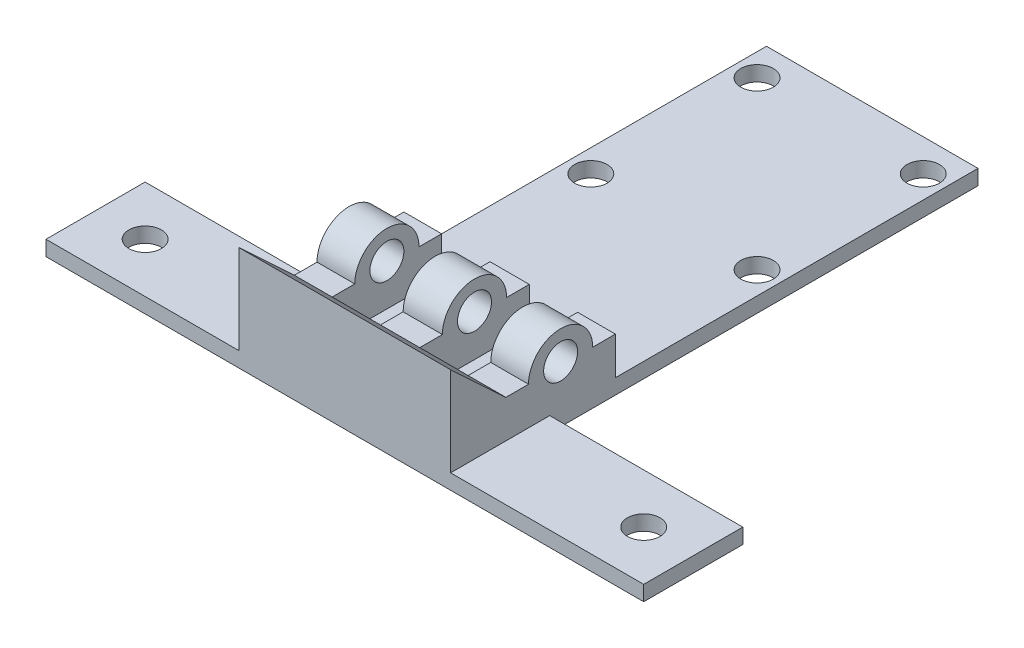
SolidWorks part; units mm, degrees
ref_plane "Front Plane" through (0, 0, 0) normal (0, 0, 1) x (1, 0, 0)
ref_plane "Top Plane" through (0, 0, 0) normal (0, 1, 0) x (1, 0, 0)
ref_plane "Right Plane" through (0, 0, 0) normal (1, 0, 0) x (0, 0, -1)
sketch "Sketch1" plane through (0, 0, 0) normal (1, 0, 0) x (0, 0, -1)
  line L0 (2.25, 1.5) -> (7.25, 1.5)
  line L1 (-2.25, -1.5) -> (2.25, -1.5)
  line L2 (-2.25, -1.5) -> (-2.25, 1.5)
  line L3 (-2.25, 1.5) -> (2.25, 1.5) construction
  line L4 (2.25, -1.5) -> (2.25, 1.5)
  line L5 (-2.25, -1.5) -> (2.25, 1.5) construction
  line L6 (-2.25, 1.5) -> (2.25, -1.5) construction
  line L7 (7.25, 1.5) -> (7.25, 8.5)
  line L8 (7.25, 8.5) -> (4.25, 8.5)
  line L9 (-2.25, 1.5) -> (-7.25, 1.5)
  line L10 (-7.25, 1.5) -> (-7.25, 8.5)
  line L11 (-7.25, 8.5) -> (-4.25, 8.5)
  line L12 (0, 1.5) -> (0, 9) construction
  line L13 (0, 11.25) -> (0, 12.75) construction
  circle A0 centre (0, 9) radius 2.25
  arc A1 (-4.25, 8.5) -> (4.25, 8.5) centre (0, 8.5) cw
  point P0 (0, 0)
  dimension "D10" = 4.5
  dimension "D11" = 1.5
  dimension "D1" = 3
  dimension "D2" = 4.5
  dimension "D3" = 5
  dimension "D4" = 5
  dimension "D5" = 7
  dimension "D6" = 7
  dimension "D7" = 3
  dimension "D8" = 3
  dimension "D9" = 7.5
extrude "Boss-Extrude1" add sketch "Sketch1" along normal mid plane 28
sketch "Sketch2" plane through (0, 0, 7.25) normal (0, 0, 1) x (1, 0, 0)
  line L0 (14, 12.75) -> (-14, 12.75) construction
  line L1 (-9, 12.75) -> (9, 12.75)
  line L2 (-9, 12.75) -> (-9, 3.5)
  line L3 (-9, 3.5) -> (9, 3.5)
  line L4 (9, 12.75) -> (9, 3.5)
  line L5 (-9, 12.75) -> (9, 3.5) construction
  line L6 (-9, 3.5) -> (9, 12.75) construction
  line L7 (-14, 12.75) -> (-14, 8.5) construction
  line L8 (14, 8.5) -> (14, 12.75) construction
  line L9 (14, 1.5) -> (-14, 1.5) construction
  point P4 (0, 8.125)
  dimension "D1" = 5
  dimension "D2" = 5
  dimension "D3" = 2
extrude "Cut-Extrude1" cut sketch "Sketch2" against normal through all
sketch "Sketch4" plane through (0, 0, 0) normal (1, 0, 0) x (0, 0, -1)
  line L5 (-4.25, 8.5) -> (-7.25, 8.5)
  line L6 (-7.25, 8.5) -> (-7.25, 3.5)
  line L7 (-7.25, 3.5) -> (7.25, 3.5)
  line L8 (7.25, 3.5) -> (7.25, 8.5)
  line L9 (7.25, 8.5) -> (4.25, 8.5)
  line L10 (-4.25, 8.5) -> (-7.25, 8.5)
  line L11 (-7.25, 8.5) -> (-7.25, 3.5)
  line L12 (-7.25, 3.5) -> (7.25, 3.5)
  line L13 (7.25, 3.5) -> (7.25, 8.5)
  line L14 (7.25, 8.5) -> (4.25, 8.5)
  circle A0 centre (0, 9) radius 2.25 construction
  arc A1 (4.25, 8.5) -> (-4.25, 8.5) centre (0, 8.5) ccw
  arc A2 (4.25, 8.5) -> (-4.25, 8.5) centre (0, 8.5) ccw
  circle A3 centre (0, 9) radius 2.25
  dimension "D1" = 0
extrude "Boss-Extrude2" add sketch "Sketch4" along normal offset from surface 6.4 and the other way offset from surface (2.6 mm away) 6.4 up to face at (9, 9, -2.25) other way up to face at (-9, 9, 2.25)
sketch "Sketch6" plane through (-14, 0, 0) normal (-1, 0, 0) x (0, 0, 1)
  line L0 (7.25, 8.5) -> (14.5635, 15.32)
  line L1 (7.25, 8.5) -> (7.25, 1.5) construction
  line L2 (7.25, 1.5) -> (14.5635, 8.32)
  line L3 (14.5635, 8.32) -> (14.5635, 15.32)
  line L4 (7.25, 8.5) -> (7.25, 1.5)
  dimension "D1" = 133
  dimension "D2" = 133
  dimension "D3" = 10
extrude "Boss-Extrude3" add sketch "Sketch6" against normal through all
sketch "Sketch7" plane through (-14, 0, 0) normal (-1, 0, 0) x (0, 0, 1)
  line L1 (-2.25, 1.5) -> (2.25, 1.5)
  line L2 (-2.25, 1.5) -> (-2.25, -1.5)
  line L3 (-2.25, -1.5) -> (2.25, -1.5)
  line L4 (2.25, 1.5) -> (2.25, -1.5)
  line L5 (-2.25, 1.5) -> (2.25, -1.5) construction
  line L6 (-2.25, -1.5) -> (2.25, 1.5) construction
  point P4 (0, 0)
extrude "Cut-Extrude2" cut sketch "Sketch7" against normal through all
sketch "Sketch9" plane through (0, 0, -7.25) normal (0, 0, -1) x (-1, 0, 0)
  line L0 (14, 1.5) -> (14, 8.5) construction
  line L1 (-14, 1.5) -> (14, 1.5)
  line L2 (-14, 1.5) -> (-14, 3.5)
  line L3 (-14, 3.5) -> (14, 3.5)
  line L4 (14, 1.5) -> (14, 3.5)
  line L5 (-14, 1.5) -> (14, 3.5) construction
  line L6 (-14, 3.5) -> (14, 1.5) construction
  line L7 (9, 3.5) -> (2.6, 3.5) construction
  point P4 (0, 2.5)
extrude "Boss-Extrude4" add sketch "Sketch9" along normal blind 48
sketch "Sketch11" plane through (0, 3.5, 0) normal (0, 1, 0) x (1, 0, 0)
  line L1 (-14, -14.5635) -> (14, -14.5635)
  line L2 (-14, -14.5635) -> (-14, -7.25)
  line L3 (-14, -7.25) -> (14, -7.25)
  line L4 (14, -14.5635) -> (14, -7.25)
  line L5 (-14, -14.5635) -> (14, -7.25) construction
  line L6 (-14, -7.25) -> (14, -14.5635) construction
  point P4 (0, -10.9068)
extrude "Boss-Extrude5" add sketch "Sketch11" against normal up to surface and the other way up to surface up to face at (0, 1.5, -24) other way up to face at (0, 4.91, 10.9068)
sketch "Sketch14" plane through (0, 3.5, 0) normal (0, 1, 0) x (1, 0, 0)
  line L0 (11, 55.25) -> (11, 51) construction
  line L1 (-14, 55.25) -> (14, 55.25) construction
  line L2 (11, 51) -> (14, 51) construction
  line L3 (14, 55.25) -> (14, 7.25) construction
  line L4 (0, 55.25) -> (0, 40) construction
  line L5 (0, 40) -> (14, 40) construction
  circle A0 centre (11, 51) radius 2.15
  circle A1 centre (11, 29) radius 2.15
  circle A2 centre (-11, 29) radius 2.15
  circle A3 centre (-11, 51) radius 2.15
  point P21 (0, 40)
  dimension "D3" = 4.3
  dimension "D1" = 3
  dimension "D2" = 4.25
  dimension "D4" = 15.25
  dimension "D5" = 4
extrude "Cut-Extrude6" cut sketch "Sketch14" against normal through all
sketch "Sketch15" plane through (14, 0, 0) normal (1, 0, 0) x (0, 0, -1)
  line L1 (7.25, 3.5) -> (-14.5635, 3.5)
  line L2 (7.25, 3.5) -> (7.25, 1.5)
  line L3 (7.25, 1.5) -> (-14.5635, 1.5)
  line L4 (-14.5635, 3.5) -> (-14.5635, 1.5)
extrude "Boss-Extrude6" add sketch "Sketch15" along normal blind 30
sketch "Sketch16" plane through (0, 3.5, 0) normal (0, 1, 0) x (1, 0, 0)
  line L0 (11, 29) -> (33, 29)
  line L1 (33, 29) -> (33, -8.0041)
  line L2 (11, 29) -> (33, -8.0041)
  circle A0 centre (33, -8.0041) radius 2.15
  dimension "D1" = 22
  dimension "D2" = 43.05
extrude "Cut-Extrude7" cut sketch "Sketch16" against normal up to surface (2 mm away) contours L2 A0 L1 | L1 A0 L2 up to face at (-11, 1.5, -48.85)
sketch "Sketch17" plane through (-14, 0, 0) normal (-1, 0, 0) x (0, 0, 1)
  line L1 (-7.25, 3.5) -> (14.5635, 3.5)
  line L2 (-7.25, 3.5) -> (-7.25, 1.5)
  line L3 (-7.25, 1.5) -> (14.5635, 1.5)
  line L4 (14.5635, 3.5) -> (14.5635, 1.5)
extrude "Boss-Extrude7" add sketch "Sketch17" along normal blind 30
sketch "Sketch19" plane through (0, 3.5, 0) normal (0, 1, 0) x (1, 0, 0)
  line L0 (-11, 29) -> (-33, 29)
  line L1 (-33, 29) -> (-33, -8)
  circle A0 centre (-33, -8) radius 2.15
  dimension "D1" = 22
  dimension "D2" = 37
extrude "Cut-Extrude8" cut sketch "Sketch19" against normal up to surface (2 mm away) up to face at (33, 1.5, 10.1541)
sketch "Sketch20" plane through (0, 3.5, 0) normal (0, 1, 0) x (1, 0, 0)
  line L0 (44, 7.25) -> (44, -14.5635) construction
  line L1 (14, 7.25) -> (44, 7.25)
  line L2 (14, 7.25) -> (14, -1.4441)
  line L3 (14, -1.4441) -> (44, -1.4441)
  line L4 (44, 7.25) -> (44, -1.4441)
  line L6 (-44, -14.5635) -> (-44, 7.25) construction
  line L7 (-14, 7.25) -> (-44, 7.25)
  line L8 (-14, 7.25) -> (-14, -1.4441)
  line L9 (-14, -1.4441) -> (-44, -1.4441)
  line L10 (-44, 7.25) -> (-44, -1.4441)
  line L11 (44, -14.5635) -> (14, -14.5635) construction
  line L12 (-44, -14.5635) -> (-39.56, -14.5635)
  line L13 (-44, -14.5635) -> (-44, -1.4441)
  line L14 (-44, -1.4441) -> (-39.56, -1.4441)
  line L15 (-39.56, -14.5635) -> (-39.56, -1.4441)
  line L16 (44, -1.4441) -> (39.56, -1.4441)
  line L17 (44, -1.4441) -> (44, -14.5635)
  line L18 (44, -14.5635) -> (39.56, -14.5635)
  line L19 (39.56, -1.4441) -> (39.56, -14.5635)
  circle A0 centre (33, -8.0041) radius 2.15 construction
  circle A1 centre (-33, -8) radius 2.15 construction
  line M5 (14, 7.25) -> (14, -14.5635)
  line M6 (14, -14.5635) -> (44, -14.5635)
  line M7 (44, -14.5635) -> (44, 7.25)
  line M8 (44, 7.25) -> (14, 7.25)
  dimension "D1" = 6.56
  dimension "D2" = 6.56
  dimension "D3" = 6.56
extrude "Cut-Extrude9" cut sketch "Sketch20" against normal up to surface (2 mm away) contours L3 M5 M7 M8 | L3 L19 M6 M7 | L7 L10 L9 L8 | L12 L15 L9 L13 up to face at (-33, 1.5, 10.15)
